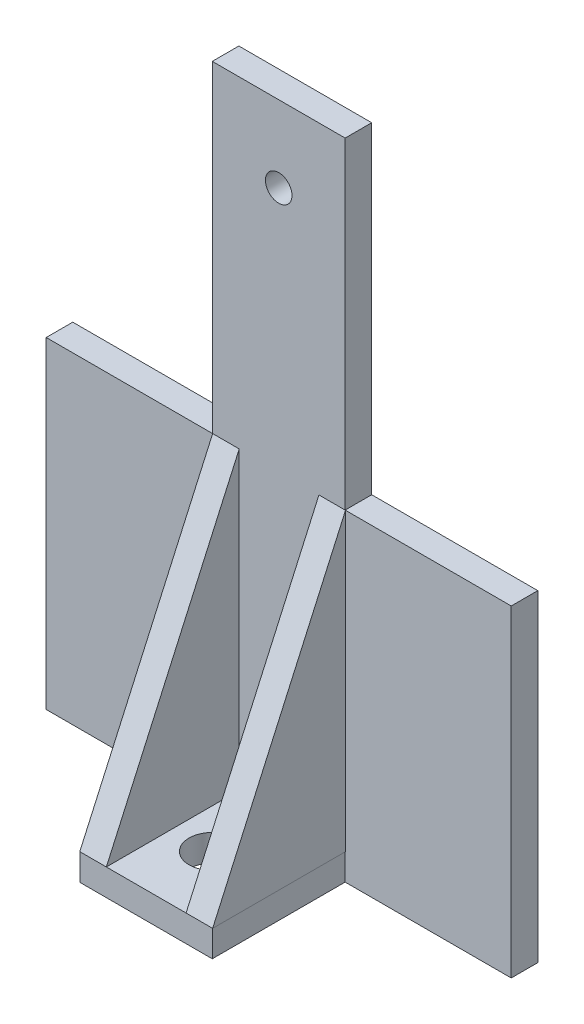
SolidWorks part; units mm, degrees
ref_plane "Plano frontal" through (0, 0, 0) normal (0, 0, 1) x (1, 0, 0)
ref_plane "Plano superior" through (0, 0, 0) normal (0, 1, 0) x (1, 0, 0)
ref_plane "Plano direito" through (0, 0, 0) normal (1, 0, 0) x (0, 0, -1)
sketch "Esboço1" plane through (0, 0, 0) normal (0, 0, 1) x (1, 0, 0)
  line L0 (4.5746, 14.0417) -> (17.0746, 14.0417)
  line L1 (-17.9254, -10.2083) -> (17.0746, -10.2083)
  line L2 (-17.9254, -10.2083) -> (-17.9254, 14.0417)
  line L3 (-5.4254, 38.2917) -> (4.5746, 38.2917)
  line L4 (17.0746, -10.2083) -> (17.0746, 14.0417)
  line L5 (-5.4254, -10.2083) -> (4.5746, -10.2083)
  line L6 (-5.4254, 14.0417) -> (-5.4254, 38.2917)
  line L7 (-5.4254, 38.2917) -> (4.5746, 38.2917)
  line L8 (4.5746, 14.0417) -> (4.5746, 38.2917)
  line L9 (-17.9254, -10.2083) -> (17.0746, -10.2083)
  line L10 (-17.9254, -10.2083) -> (-17.9254, 14.0417)
  line L11 (-17.9254, 14.0417) -> (-5.4254, 14.0417)
  line L12 (17.0746, -10.2083) -> (17.0746, 14.0417)
  circle A0 centre (-0.4254, -4.4583) radius 1
  circle A1 centre (-0.4254, 32.5417) radius 1
  dimension "D2" = 17.5
  dimension "D5" = 5.75
  dimension "D1" = 35
  dimension "D3" = 5.75
  dimension "D6" = 10
  dimension "D7" = 5
extrude "Ressalto-extrusão1" add sketch "Esboço1" along normal blind 2 contours L11 L2 L1 L4 L0 L8 L3 L6 A1 A0
sketch "Esboço2" plane through (0, 0, 2) normal (0, 0, 1) x (1, 0, 0)
  line L0 (17.0746, -10.2083) -> (17.0746, 14.0417) construction
  line L1 (-17.9254, -10.2083) -> (17.0746, -10.2083)
  line L2 (-17.9254, -10.2083) -> (-17.9254, -8.2083)
  line L3 (-17.9254, -8.2083) -> (17.0746, -8.2083)
  line L4 (17.0746, -10.2083) -> (17.0746, -8.2083)
  dimension "D1" = 2
extrude "Ressalto-extrusão2" add sketch "Esboço2" along normal blind 10
sketch "Esboço3" plane through (0, -8.2083, 0) normal (0, 1, 0) x (1, 0, 0)
  line L0 (-17.9254, -12) -> (17.0746, -2) construction
  line L1 (17.0746, -2) -> (17.0746, -12) construction
  line L2 (17.0746, -12) -> (-17.9254, -2) construction
  circle A0 centre (-0.4254, -7) radius 1.75
extrude "Corte-extrusão1" cut sketch "Esboço3" against normal blind 10
sketch "Esboço4" plane through (0, -8.2083, 0) normal (0, 1, 0) x (1, 0, 0)
  line L0 (17.0746, -2) -> (-17.9254, -2) construction
  line L1 (-17.9254, -12) -> (-5.3982, -12)
  line L2 (-17.9254, -12) -> (-17.9254, -2)
  line L3 (-17.9254, -2) -> (-5.3982, -2)
  line L4 (-5.3982, -12) -> (-5.3982, -2)
  line L6 (17.0746, -12) -> (4.5746, -12)
  line L7 (17.0746, -12) -> (17.0746, -2)
  line L8 (17.0746, -2) -> (4.5746, -2)
  line L9 (4.5746, -12) -> (4.5746, -2)
extrude "Corte-extrusão2" cut sketch "Esboço4" against normal blind 10
sketch "Esboço5" plane through (-5.3982, 0, 0) normal (-1, 0, 0) x (0, 0, 1)
  line L0 (12, -8.2083) -> (2, 14.0417)
  line L6 (2, 14.0417) -> (2, -8.2083)
  line L7 (2, -8.2083) -> (12, -8.2083)
extrude "Ressalto-extrusão3" add sketch "Esboço5" against normal blind 10
sketch "Esboço6" plane through (0, 0, 12) normal (0, 0, 1) x (1, 0, 0)
  line L1 (-3.3982, -8.2083) -> (2.6018, -8.2083)
  line L2 (-3.3982, -8.2083) -> (-3.3982, 14.0417)
  line L3 (-3.3982, 14.0417) -> (2.6018, 14.0417)
  line L4 (2.6018, -8.2083) -> (2.6018, 14.0417)
  line L5 (4.5746, 14.0417) -> (-5.3982, 14.0417) construction
  line L6 (-5.3982, -8.2083) -> (-5.3982, 14.0417) construction
  line L7 (4.6018, -8.2083) -> (4.6018, 14.0417) construction
  line L8 (4.5746, -8.2083) -> (-5.3982, -8.2083) construction
  dimension "D1" = 2
  dimension "D2" = 2
extrude "Corte-extrusão3" cut sketch "Esboço6" against normal blind 10
